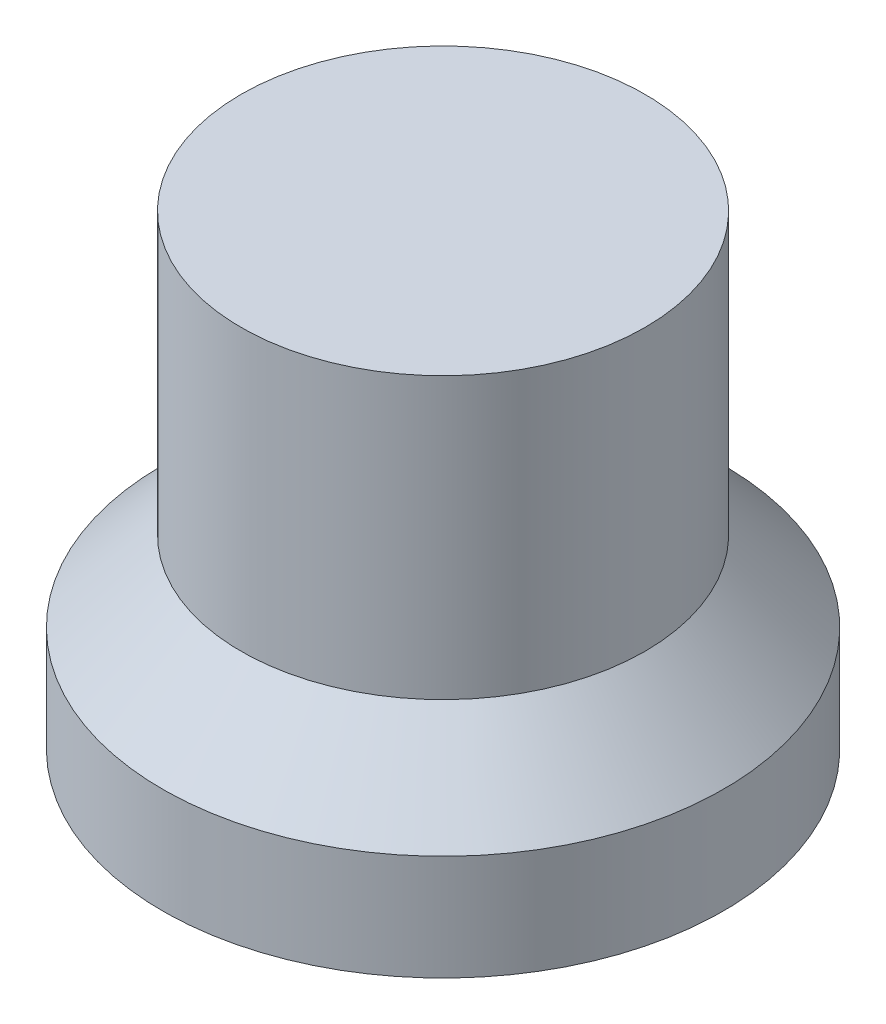
SolidWorks part; units mm, degrees
ref_plane "Alzado" through (0, 0, 0) normal (0, 0, 1) x (1, 0, 0)
ref_plane "Planta" through (0, 0, 0) normal (0, 1, 0) x (1, 0, 0)
ref_plane "Vista lateral" through (0, 0, 0) normal (1, 0, 0) x (0, 0, -1)
sketch "Croquis1" plane through (0, 0, 0) normal (0, 0, 1) x (1, 0, 0)
  line L0 (0, 0) -> (-9, 0)
  line L1 (-9, 0) -> (-9, -12.5)
  line L2 (-9, -12.5) -> (-12.5, -16.0707)
  line L3 (-12.5, -16.0707) -> (-12.5, -20.7707)
  line L4 (-12.5, -20.7707) -> (0, -20.7707)
  line L5 (0, 0) -> (0, -20.7707) construction
  line L6 (0, 0) -> (0, -20.7707)
  dimension "D1" = 9
  dimension "D2" = 12.5
  dimension "D3" = 5
  dimension "D4" = 4.7
  dimension "D5" = 12.5
revolve "Revolución1" add sketch "Croquis1" angle 360 about L5
